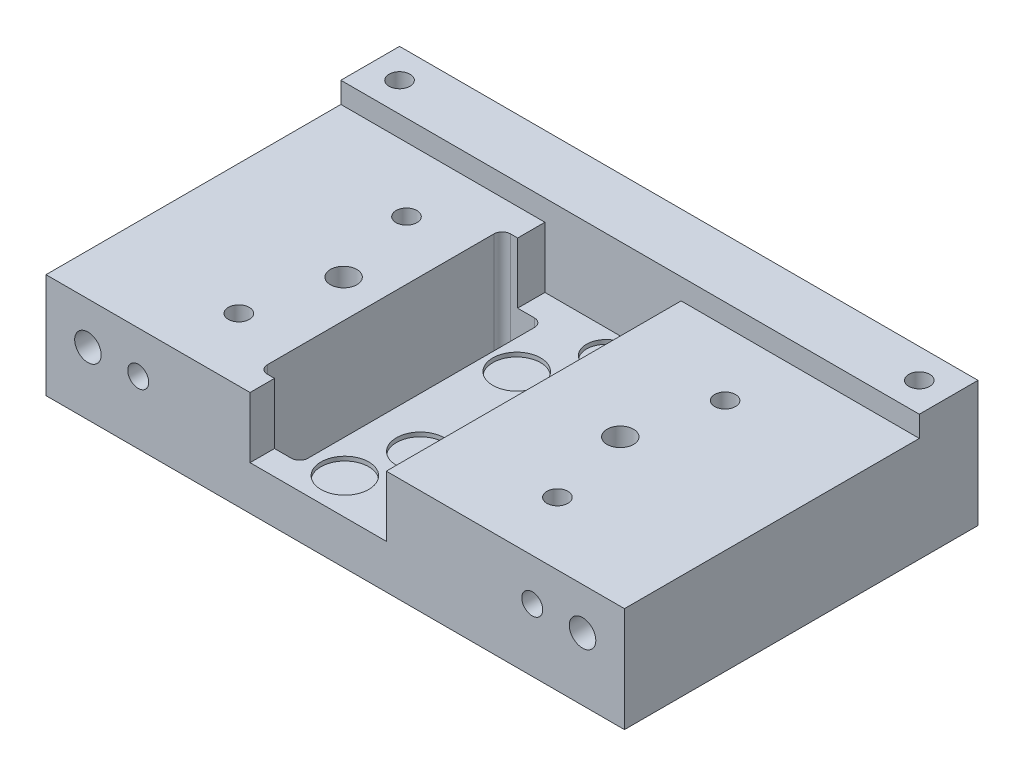
SolidWorks part; units mm, degrees
material "6061-T6 (SS)"
ref_plane "Front Plane" through (0, 0, 0) normal (0, 0, 1) x (1, 0, 0)
ref_plane "Top Plane" through (0, 0, 0) normal (0, 1, 0) x (1, 0, 0)
ref_plane "Right Plane" through (0, 0, 0) normal (1, 0, 0) x (0, 0, -1)
sketch "Sketch1" plane through (0, 0, 0) normal (0, 1, 0) x (1, 0, 0)
  line L1 (0, 0) -> (55, 0)
  line L2 (0, 0) -> (0, 42.17)
  line L3 (0, 42.17) -> (55, 42.17)
  line L4 (55, 0) -> (55, 42.17)
  dimension "D1" = 55
  dimension "D2" = 42.17
extrude "Boss-Extrude1" add sketch "Sketch1" along normal blind 12.5
sketch "Sketch2" plane through (0, 12.5, 0) normal (0, 1, 0) x (1, 0, 0)
  line L0 (55, 0) -> (55, 42.17) construction
  line L1 (0, 42.17) -> (55, 42.17)
  line L2 (0, 42.17) -> (0, 35.17)
  line L3 (0, 35.17) -> (55, 35.17)
  line L4 (55, 42.17) -> (55, 35.17)
  dimension "D1" = 7
extrude "Boss-Extrude2" add sketch "Sketch2" along normal blind 2.5
sketch "Sketch3" plane through (0, 12.5, 0) normal (0, 1, 0) x (1, 0, 0)
  line L1 (33.59, 0) -> (17.34, 0)
  line L2 (33.59, 0) -> (33.59, 35.17)
  line L3 (33.59, 35.17) -> (17.34, 35.17)
  line L4 (17.34, 0) -> (17.34, 35.17)
  line L7 (55, 0) -> (55, 35.17) construction
  line L8 (0, 35.17) -> (0, 0) construction
  dimension "D1" = 16.25
  dimension "D2" = 21.41
  dimension "D3" = 35.17
  dimension "D4" = 17.34
  dimension "D5" = 16.25
extrude "Cut-Extrude1" cut sketch "Sketch3" against normal blind 7.25
sketch "Sketch4" plane through (0, 12.5, 0) normal (0, 1, 0) x (1, 0, 0)
  line L1 (15.5, 3.9173) -> (15.5, 30.9173)
  line L2 (16.5, 31.9173) -> (19.34, 31.9173)
  line L3 (20.34, 30.9173) -> (20.34, 3.9173)
  line L4 (19.34, 2.9173) -> (16.5, 2.9173)
  line L5 (17.34, 0) -> (33.59, 0) construction
  line L6 (55, 0) -> (55, 35.17) construction
  arc A0 (15.5, 30.9173) -> (16.5, 31.9173) centre (16.5, 30.9173) cw
  arc A1 (19.34, 31.9173) -> (20.34, 30.9173) centre (19.34, 30.9173) cw
  arc A3 (19.34, 2.9173) -> (20.34, 3.9173) centre (19.34, 3.9173) ccw
  arc A5 (16.5, 2.9173) -> (15.5, 3.9173) centre (16.5, 3.9173) cw
  dimension "D1" = 27
  dimension "D2" = 29
  dimension "D3" = 27
  dimension "D4" = 4.84
  dimension "D5" = 2.84
  dimension "D6" = 2.84
  dimension "D7" = 2.9173
  dimension "D8" = 34.66
extrude "Cut-Extrude2" cut sketch "Sketch4" against normal through all
sketch "Sketch5" plane through (0, 5.25, 0) normal (0, 1, 0) x (1, 0, 0)
  line L1 (0, 35.17) -> (55, 35.17) construction
  line L2 (55, 0) -> (55, 35.17) construction
  circle A0 centre (24.34, 4.3073) radius 2.85
  circle A1 centre (26.34, 11.3073) radius 2.85
  circle A2 centre (29.84, 18.3073) radius 2.85
  circle A3 centre (23.84, 25.3073) radius 2.85
  circle A4 centre (27.52, 32.3073) radius 2.35
  dimension "D1" = 5.7
  dimension "D2" = 5.7
  dimension "D3" = 5.7
  dimension "D4" = 5.7
  dimension "D5" = 4.7
  dimension "D6" = 2.8627
  dimension "D7" = 7
  dimension "D8" = 7
  dimension "D9" = 7
  dimension "D10" = 7
  dimension "D11" = 3.68
  dimension "D12" = 6
  dimension "D13" = 3.5
  dimension "D14" = 2
  dimension "D15" = 27.48
extrude "Cut-Extrude3" cut sketch "Sketch5" against normal blind 0.5
sketch "Sketch7" plane through (0, 0, 0) normal (0, -1, 0) x (1, 0, 0)
  line L0 (55, -42.17) -> (0, -42.17) construction
  line L1 (55, 0) -> (55, -42.17) construction
  circle A0 centre (27.52, -32.3073) radius 5
  dimension "D1" = 9.8627
  dimension "D2" = 27.48
  dimension "D3" = 10
extrude "Boss-Extrude3" add sketch "Sketch7" along normal blind 4
sketch "Sketch8" plane through (0, -4, 0) normal (0, -1, 0) x (1, 0, 0)
  point P0 (27.52, -32.3073)
hole_wizard "Tap Drill for #10-32 Tap1" positions "Sketch9" profile "Sketch10" hole size "#10-32" standard "ANSI Inch"
sketch "Sketch9" plane through (0, -4, 0) normal (0, -1, 0) x (-1, 0, 0)
  point P0 (-27.52, 32.3073)
sketch "Sketch10" plane through (27.52, -4, -32.3073) normal (1, 0, 0) x (0, 0, -1)
  line L0 (0, 0) -> (0, 5.2133)
  line L1 (0, 5.2133) -> (2.0193, 4)
  line L2 (2.0193, 4) -> (2.0193, 0.635)
  line L3 (2.0193, 0.635) -> (2.6543, 0)
  line L5 (2.6543, 0) -> (0, 0)
  line L6 (-2.0193, 0.635) -> (-2.6543, 0) construction
  line L10 (0, 5.2133) -> (-2.0193, 4) construction
  line L11 (0, -6.35) -> (0, 107.95) construction
  dimension "Hole Dia." = 4.0386
  dimension "Hole Depth" = 4
  dimension "Near C'Sink Dia." = 5.3086
  dimension "Near C'Sink Angle" = 90
  dimension "Drill Angle" = 118
sketch "Sketch11" plane through (0, 4.75, 0) normal (0, 1, 0) x (1, 0, 0)
  circle A0 centre (27.52, 32.3073) radius 1
  dimension "D1" = 2
extrude "Cut-Extrude4" cut sketch "Sketch11" against normal through all
sketch "Sketch12" plane through (0, 12.5, 0) normal (0, 1, 0) x (1, 0, 0)
  line L0 (55, 0) -> (55, 35.17) construction
  line L2 (0, 35.17) -> (0, 0) construction
  line L6 (0, 0) -> (17.34, 0) construction
  line L7 (33.59, 0) -> (55, 0) construction
  circle A0 centre (8.5, 27.5) radius 1.25
  circle A1 centre (8.5, 7.5) radius 1.25
  circle A2 centre (46.5, 7.5) radius 1.25
  circle A3 centre (46.5, 27.5) radius 1.25
  dimension "D1" = 2.5
  dimension "D2" = 2.5
  dimension "D3" = 2.5
  dimension "D4" = 2.5
  dimension "D5" = 8.5
  dimension "D6" = 8.5
  dimension "D7" = 20
  dimension "D8" = 7.5
  dimension "D9" = 20
  dimension "D10" = 8.5
  dimension "D11" = 8.5
  dimension "D12" = 7.5
hole_wizard "Tap Drill for M3x0.5 Tap1" positions "Sketch13" profile "Sketch14" hole size "M3x0.5" standard "ANSI Metric" end condition through all
sketch "Sketch13" plane through (0, 12.5, 0) normal (0, 1, 0) x (1, 0, 0)
  point P0 (8.5, 7.5)
  point P3 (8.5, 27.5)
  point P6 (46.5, 27.5)
  point P9 (46.5, 7.5)
sketch "Sketch14" plane through (8.5, 12.5, -7.5) normal (1, 0, 0) x (0, 0, 1)
  line L0 (0, 0) -> (0, 16.5)
  line L1 (0, 16.5) -> (1.25, 16.5)
  line L2 (1.25, 16.5) -> (1.25, 0)
  line L5 (1.25, 0) -> (0, 0)
  line L11 (0, -6.35) -> (0, 107.95) construction
  dimension "Thru Hole Dia." = 2.5
  dimension "Thru Hole Depth" = 16.5
sketch "Sketch15" plane through (0, 12.5, 0) normal (0, 1, 0) x (1, 0, 0)
  line L0 (55, 0) -> (55, 35.17) construction
  line L2 (0, 35.17) -> (0, 0) construction
  circle A0 centre (11, 17.5) radius 1.58
  circle A1 centre (44, 17.5) radius 1.58
  circle A2 centre (8.5, 7.5) radius 1.25 construction
  circle A5 centre (46.5, 7.5) radius 1.25 construction
  dimension "D1" = 3.16
  dimension "D2" = 3.16
  dimension "D3" = 11
  dimension "D4" = 10
  dimension "D5" = 11
  dimension "D6" = 10
extrude "Cut-Extrude5" cut sketch "Sketch15" against normal through all
sketch "Sketch19" plane through (0, 0, 0) normal (0, 0, 1) x (1, 0, 0)
  line L0 (55, 12.5) -> (55, 0) construction
  line L1 (0, 0) -> (55, 0) construction
  line L2 (0, 12.5) -> (0, 0) construction
  circle A0 centre (4, 7.5) radius 1.25
  circle A1 centre (51, 7.5) radius 1.25
  dimension "D1" = 2.5
  dimension "D2" = 2.5
  dimension "D3" = 4
  dimension "D4" = 7.5
  dimension "D5" = 7.5
  dimension "D6" = 4
hole_wizard "Tap Drill for M3x0.5 Tap3" positions "Sketch20" profile "Sketch21" hole size "M3x0.5" standard "ANSI Metric"
sketch "Sketch20" plane through (0, 0, 0) normal (0, 0, 1) x (1, 0, 0)
  point P0 (4, 7.5)
  point P3 (51, 7.5)
sketch "Sketch21" plane through (4, 7.5, 0) normal (1, 0, 0) x (0, -1, 0)
  line L0 (0, 0) -> (0, 10.7511)
  line L1 (0, 10.7511) -> (1.25, 10)
  line L2 (1.25, 10) -> (1.25, 0)
  line L5 (1.25, 0) -> (0, 0)
  line L10 (0, 10.7511) -> (-1.25, 10) construction
  line L11 (0, -6.35) -> (0, 107.95) construction
  dimension "Hole Dia." = 2.5
  dimension "Hole Depth" = 10
  dimension "Drill Angle" = 118
sketch "Sketch22" plane through (55, 0, 0) normal (1, 0, 0) x (0, 0, -1)
  line L0 (0, 0) -> (42.17, 0)
  line L1 (42.17, 0) -> (42.17, 15)
  line L2 (42.17, 15) -> (35.17, 15)
  line L3 (35.17, 15) -> (35.17, 12.5)
  line L4 (35.17, 12.5) -> (0, 12.5)
  line L5 (0, 12.5) -> (0, 0)
extrude "Boss-Extrude4" add sketch "Sketch22" along normal blind 7
sketch "Sketch23" plane through (0, 0, 0) normal (-1, 0, 0) x (0, 0, 1)
  line L0 (0, 0) -> (0, 12.5)
  line L1 (0, 12.5) -> (-35.17, 12.5)
  line L2 (-35.17, 12.5) -> (-35.17, 15)
  line L3 (-35.17, 15) -> (-42.17, 15)
  line L4 (-42.17, 15) -> (-35.17, 15) construction
  line L5 (-42.17, 15) -> (-42.17, 0)
  line L6 (-42.17, 0) -> (0, 0) construction
  line L7 (-42.17, 0) -> (0, 0)
extrude "Boss-Extrude5" add sketch "Sketch23" along normal blind 7
sketch "Sketch24" plane through (0, 0, 0) normal (0, 0, 1) x (1, 0, 0)
  line L1 (-7, 0) -> (62, 0) construction
  circle A0 centre (57, 7.5) radius 1.58
  circle A1 centre (-2, 7.5) radius 1.58
  circle A2 centre (51, 7.5) radius 1.25 construction
  circle A3 centre (4, 7.5) radius 1.25 construction
  dimension "D1" = 3.16
  dimension "D2" = 3.16
  dimension "D3" = 6
  dimension "D4" = 6
  dimension "D5" = 7.5
  dimension "D6" = 7.5
extrude "Cut-Extrude6" cut sketch "Sketch24" against normal blind 10
sketch "Sketch16" plane through (0, 15, 0) normal (0, 1, 0) x (1, 0, 0)
  line L1 (62, 42.17) -> (-7, 42.17) construction
  line L3 (-7, 35.17) -> (-7, 42.17) construction
  line L4 (62, 42.17) -> (62, 35.17) construction
  circle A0 centre (-3.5, 38.67) radius 1.25
  circle A1 centre (58.5, 38.67) radius 1.25
  dimension "D1" = 3.5
  dimension "D2" = 3.5
  dimension "D3" = 3.5
  dimension "D4" = 3.5
  dimension "D5" = 2.5
  dimension "D6" = 2.5
hole_wizard "Tap Drill for M3x0.5 Tap2" positions "Sketch17" profile "Sketch18" hole size "M3x0.5" standard "ANSI Metric" end condition through all
sketch "Sketch17" plane through (0, 15, 0) normal (0, 1, 0) x (1, 0, 0)
  point P0 (-3.5, 38.67)
  point P3 (58.5, 38.67)
sketch "Sketch18" plane through (-3.5, 15, -38.67) normal (1, 0, 0) x (0, 0, 1)
  line L0 (0, 0) -> (0, 19)
  line L1 (0, 19) -> (1.25, 19)
  line L2 (1.25, 19) -> (1.25, 0)
  line L5 (1.25, 0) -> (0, 0)
  line L11 (0, -6.35) -> (0, 107.95) construction
  dimension "Thru Hole Dia." = 2.5
  dimension "Thru Hole Depth" = 19
